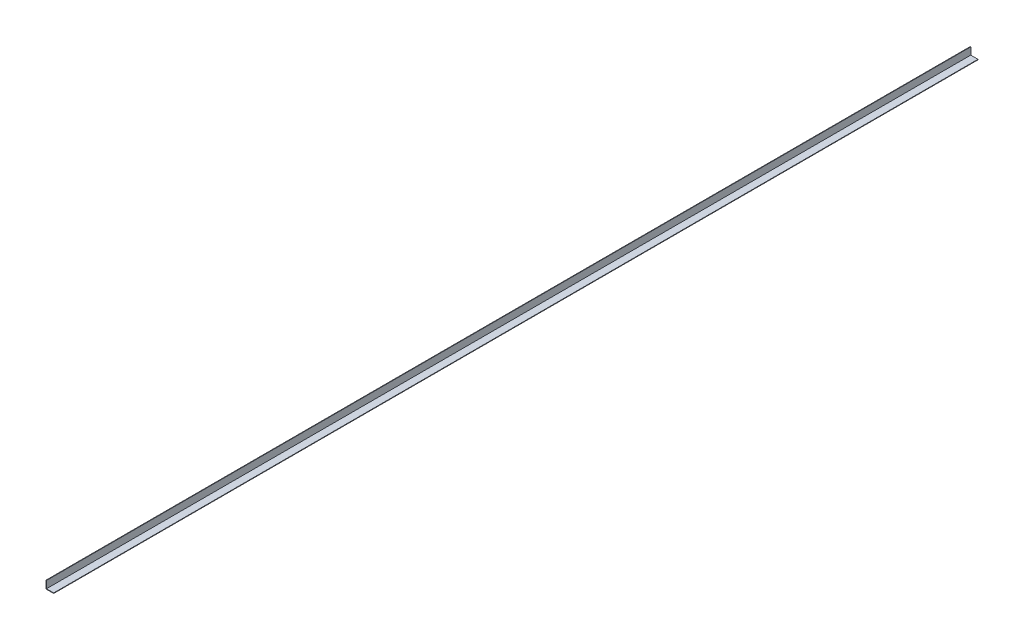
SolidWorks part; units mm, degrees
material "ASTM A36 Acero"
ref_plane "Alzado" through (0, 0, 0) normal (0, 0, 1) x (1, 0, 0)
ref_plane "Planta" through (0, 0, 0) normal (0, 1, 0) x (1, 0, 0)
ref_plane "Vista lateral" through (0, 0, 0) normal (1, 0, 0) x (0, 0, -1)
sketch "Croquis1" plane through (0, 0, 0) normal (0, 0, 1) x (1, 0, 0)
  line L0 (0, 50.8) -> (0, 0)
  line L1 (0, 0) -> (50.8, 0)
  line L2 (50.8, 0) -> (50.8, 3.18)
  line L3 (50.8, 3.18) -> (3.18, 3.18)
  line L4 (3.18, 3.18) -> (3.18, 50.8)
  line L5 (3.18, 50.8) -> (0, 50.8)
  dimension "D1" = 3.18
  dimension "D2" = 50.8
extrude "Saliente-Extruir1" add sketch "Croquis1" against normal blind 6100
